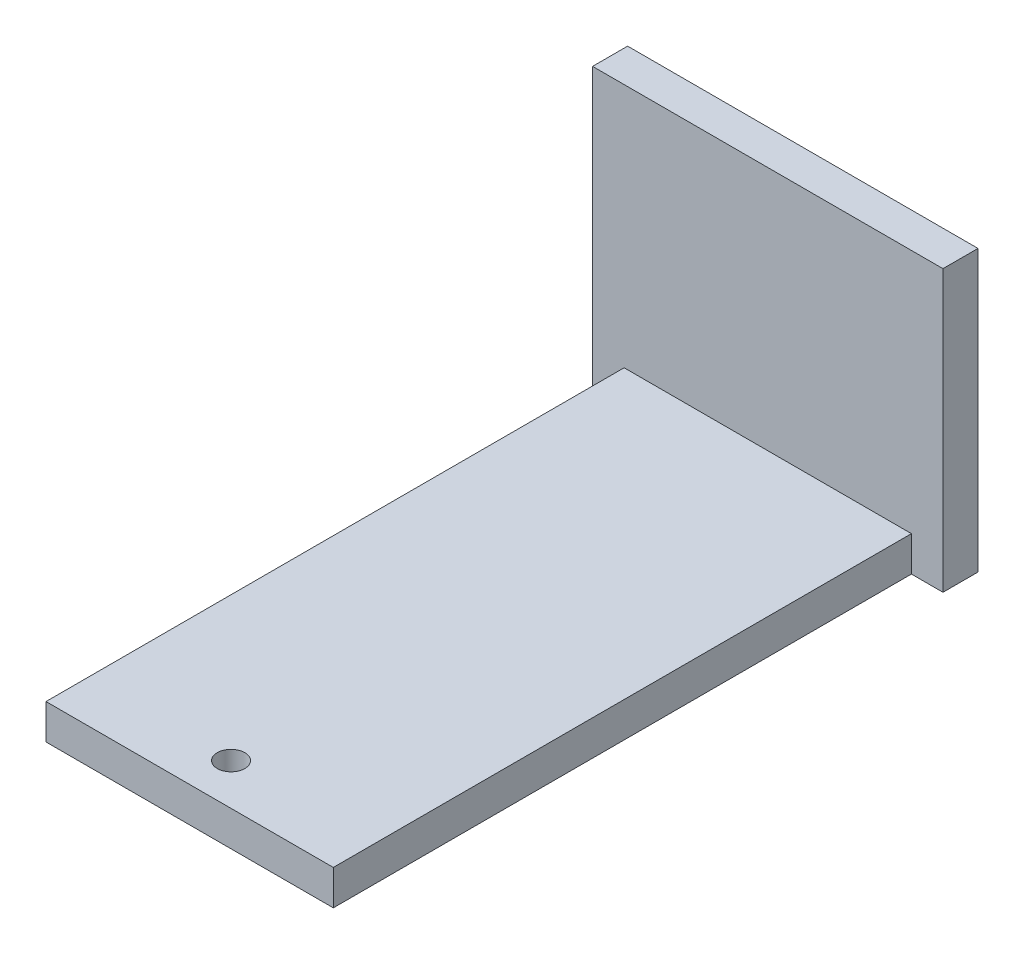
SolidWorks part; units mm, degrees
ref_plane "Front Plane" through (0, 0, 0) normal (0, 0, 1) x (1, 0, 0)
ref_plane "Top Plane" through (0, 0, 0) normal (0, 1, 0) x (1, 0, 0)
ref_plane "Right Plane" through (0, 0, 0) normal (1, 0, 0) x (0, 0, -1)
sketch "Sketch1" plane through (0, 0, 0) normal (0, 0, 1) x (1, 0, 0)
  line L1 (0, 0) -> (25.4, 0)
  line L2 (0, 0) -> (0, -25.4)
  line L3 (0, -25.4) -> (25.4, -25.4)
  line L4 (25.4, 0) -> (25.4, -25.4)
  dimension "D1" = 25.4
  dimension "D2" = 25.4
extrude "Boss-Extrude1" add sketch "Sketch1" along normal blind 2.54
ref_plane "Plane1" through (0, -19.05, 0) normal (0, 1, 0) x (1, 0, 0)
sketch "Sketch2" plane through (0, -19.05, 0) normal (0, 1, 0) x (1, 0, 0)
  line L0 (25.4, -2.54) -> (0, -2.54) construction
  line L1 (2.286, -44.45) -> (2.286, -2.54)
  line L2 (2.286, -2.54) -> (12.7, -2.54)
  line L3 (12.7, -2.54) -> (23.114, -2.54)
  line L4 (23.114, -2.54) -> (23.114, -44.45)
  line L5 (2.286, -44.45) -> (23.114, -44.45)
  point P13 (12.7, -2.54)
  dimension "D2" = 41.91
extrude "Boss-Extrude3" add sketch "Sketch2" along normal mid plane 2.54 contours L5 L2 L1 | L5 L4 L3
sketch "Sketch3" plane through (0, -17.78, 0) normal (0, 1, 0) x (1, 0, 0)
  line L0 (2.286, -44.45) -> (4.826, -44.45)
  line L1 (20.574, -44.45) -> (23.114, -44.45)
  arc A0 (2.286, -44.45) -> (23.114, -44.45) centre (12.7, -44.45) cw
  arc A1 (4.826, -44.45) -> (20.574, -44.45) centre (12.7, -44.45) cw
  dimension "D1" = 2.54
extrude "Boss-Extrude4" [suppressed] add sketch "Sketch3" against normal blind 0.635
mirror "Mirror1" [suppressed] about plane through (0, -19.05, 0) normal (0, 1, 0)
sketch "Sketch4" [suppressed] plane through (2.286, 0, 0) normal (-1, 0, 0) x (0, 0, 1)
  line L1 (2.54, -16.51) -> (35.56, -16.51)
  line L2 (2.54, -16.51) -> (2.54, -21.59)
  line L3 (2.54, -21.59) -> (35.56, -21.59)
  line L4 (35.56, -16.51) -> (35.56, -21.59)
extrude "Boss-Extrude5" [suppressed] add sketch "Sketch4" along normal up to surface (2.286 mm away)
sketch "Sketch5" [suppressed] plane through (23.114, 0, 0) normal (1, 0, 0) x (0, 0, -1)
  line L1 (-35.56, -16.51) -> (-2.54, -16.51)
  line L2 (-35.56, -16.51) -> (-35.56, -21.59)
  line L3 (-35.56, -21.59) -> (-2.54, -21.59)
  line L4 (-2.54, -16.51) -> (-2.54, -21.59)
extrude "Boss-Extrude6" [suppressed] add sketch "Sketch5" along normal up to surface (2.286 mm away)
sketch "Sketch6" plane through (0, 0, 44.45) normal (0, 0, 1) x (1, 0, 0)
  line L0 (25.4, -25.4) -> (25.4, 0) construction
  line L1 (0, -25.4) -> (25.4, -25.4)
  line L2 (0, -25.4) -> (0, -20.32)
  line L3 (0, -20.32) -> (25.4, -20.32)
  line L4 (25.4, -25.4) -> (25.4, -20.32)
  line L5 (2.286, -20.32) -> (23.114, -20.32) construction
extrude "Cut-Extrude1" cut sketch "Sketch6" against normal through all
sketch "Sketch7" plane through (0, -20.32, 0) normal (0, -1, 0) x (-1, 0, 0)
  line L0 (-23.114, -2.54) -> (-23.114, -44.45) construction
  line L1 (-2.286, -44.45) -> (-23.114, -44.45) construction
  circle A0 centre (-12.7, -41.45) radius 1
  dimension "D2" = 2
  dimension "D1" = 10.414
  dimension "D3" = 3
extrude "Cut-Extrude2" cut sketch "Sketch7" against normal through all
